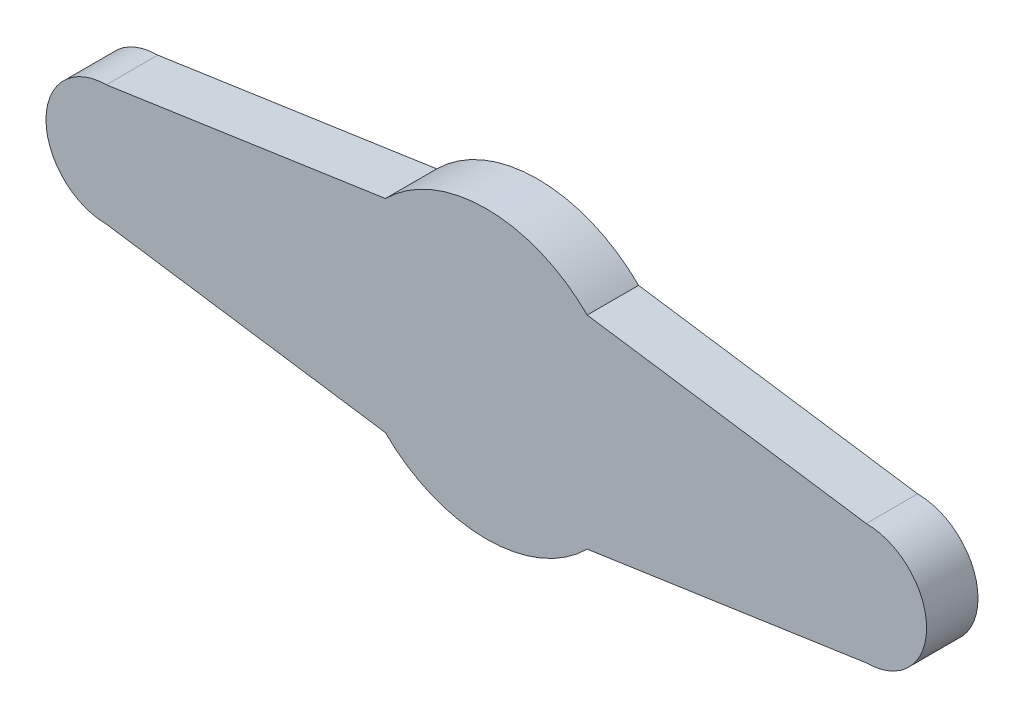
SolidWorks part; units mm, degrees
ref_plane "Front Plane" through (0, 0, 0) normal (0, 0, 1) x (1, 0, 0)
ref_plane "Top Plane" through (0, 0, 0) normal (0, 1, 0) x (1, 0, 0)
ref_plane "Right Plane" through (0, 0, 0) normal (1, 0, 0) x (0, 0, -1)
sketch "Sketch1" plane through (0, 0, 0) normal (0, 0, 1) x (1, 0, 0)
  line L0 (-17, 0) -> (17, 0)
  line L4 (17, -2.7) -> (0, -5.2)
  line L6 (0, -6.4) -> (0, 6.4)
  line L7 (-10.5, 0) -> (-7.7, 0)
  line L8 (-13.3, 0) -> (-10.5, 0)
  line L9 (-17, 0) -> (-13.3, 0)
  line L12 (-17, 2.7) -> (0, 5.2)
  line L13 (-17, -2.7) -> (0, -5.2)
  line L14 (17, 2.7) -> (0, 5.2)
  line L19 (17, 0) -> (13.3, 0)
  line L20 (13.3, 0) -> (10.5, 0)
  line L21 (10.5, 0) -> (7.7, 0)
  circle A7 centre (0, 0) radius 1.64
  circle A8 centre (-7.7, 0) radius 0.75
  circle A9 centre (-10.5, 0) radius 0.75
  circle A10 centre (-13.3, 0) radius 0.75
  circle A11 centre (-17, 0) radius 0.75
  arc A12 (-17, -2.7) -> (-16.7939, 2.6921) centre (-17, 0) cw
  circle A13 centre (-17, 0) radius 2.7
  circle A16 centre (0, 0) radius 6.4
  circle A17 centre (17, 0) radius 2.7
  arc A18 (17, -2.7) -> (16.7939, 2.6921) centre (17, 0) ccw
  circle A19 centre (17, 0) radius 0.75
  circle A20 centre (13.3, 0) radius 0.75
  circle A21 centre (10.5, 0) radius 0.75
  circle A22 centre (7.7, 0) radius 0.75
extrude "Boss-Extrude1" add sketch "Sketch1" along normal blind 2.3
